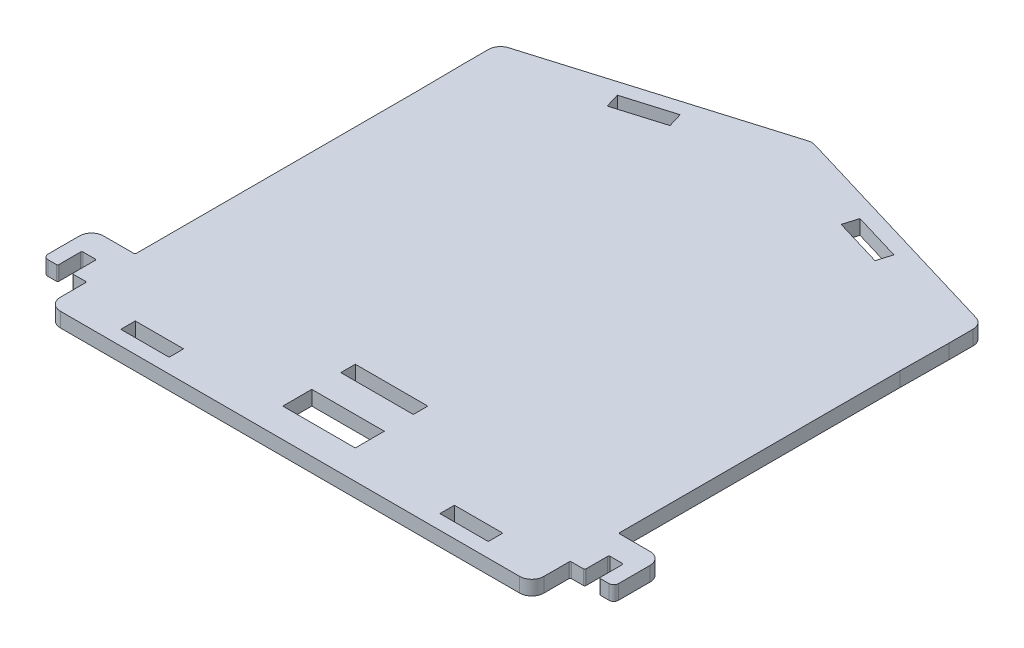
SolidWorks part; units mm, degrees
ref_plane "Alzado" through (0, 0, 0) normal (0, 0, 1) x (1, 0, 0)
ref_plane "Planta" through (0, 0, 0) normal (0, 1, 0) x (1, 0, 0)
ref_plane "Vista lateral" through (0, 0, 0) normal (1, 0, 0) x (0, 0, -1)
sketch "Croquis3" plane through (0, 0, 0) normal (0, 1, 0) x (1, 0, 0)
  line L3 (-50, -45) -> (50, -45)
  line L5 (-50, 45) -> (50, -45) construction
  line L6 (-50, -45) -> (50, 45) construction
  line L7 (-48.3179, 45.5346) -> (-0.6155, 59.8352)
  line L17 (0, 7.5742) -> (0, -7.5742) construction
  line L18 (-8.1342, 0) -> (8.1342, 0) construction
  line L19 (50, -30.05) -> (50, 28.1899)
  line L20 (56.5, -30.05) -> (50, -30.05)
  line L21 (59, -40.05) -> (59, -32.55)
  line L26 (56, -40.05) -> (59, -40.05)
  line L27 (56, -35.05) -> (56, -40.05)
  line L36 (-24.4667, 52.6849) -> (-23.5953, 49.7782) construction
  line L45 (50.1, 38.1899) -> (50, 28.1899)
  line L53 (-50.1, 43.1399) -> (-50.1, 38.1899)
  line L69 (-23.5953, 49.7782) -> (-18.5953, 51.2772)
  line L70 (-18.5953, 51.2772) -> (-17.696, 48.2772)
  line L71 (-23.5953, 49.7782) -> (-28.5953, 48.2793)
  line L72 (-28.5953, 48.2793) -> (-27.696, 45.2793)
  line L73 (-27.696, 45.2793) -> (-17.696, 48.2772)
  line L74 (28.5953, 48.2793) -> (27.696, 45.2793)
  line L75 (23.5953, 49.7782) -> (28.5953, 48.2793)
  line L76 (23.5953, 49.7782) -> (18.5953, 51.2772)
  line L77 (18.5953, 51.2772) -> (17.696, 48.2772)
  line L78 (27.696, 45.2793) -> (17.696, 48.2772)
  line L79 (48.3179, 45.5346) -> (0.6155, 59.8352)
  line L80 (50.1, 43.1399) -> (50.1, 38.1899)
  line L81 (-50.1, 38.1899) -> (-50, 28.1899)
  line L82 (53, -35.05) -> (56, -35.05)
  line L83 (53, -40.05) -> (53, -35.05)
  line L84 (-50, -45) -> (-50, -40.05)
  line L85 (-50, -40.05) -> (-53, -40.05)
  line L86 (-53, -40.05) -> (-53, -35.05)
  line L87 (-53, -35.05) -> (-56, -35.05)
  line L88 (-56, -35.05) -> (-56, -40.05)
  line L89 (-56, -40.05) -> (-59, -40.05)
  line L90 (-59, -40.05) -> (-59, -32.55)
  line L91 (-56.5, -30.05) -> (-50, -30.05)
  line L92 (-50, -30.05) -> (-50, 28.1899)
  line L93 (50, -40.05) -> (53, -40.05)
  line L94 (50, -45) -> (50, -40.05)
  arc A5 (-48.3179, 45.5346) -> (-50.1, 43.1399) centre (-47.6, 43.1399) ccw
  arc A9 (48.3179, 45.5346) -> (50.1, 43.1399) centre (47.6, 43.1399) cw
  arc A10 (-0.6155, 59.8352) -> (0.6155, 59.8352) centre (0, 57.2969) cw
  arc A11 (59, -32.55) -> (56.5, -30.05) centre (56.5, -32.55) ccw
  arc A12 (-59, -32.55) -> (-56.5, -30.05) centre (-56.5, -32.55) cw
  point P0 (0, 0)
  point P16 (0, 0)
  point P18 (0, 0)
  point P29 (0, 0)
  point P34 (-59, -30.05)
  point P53 (0, 60)
  point P59 (-23.5953, 49.7782)
  point P60 (-23.5953, 49.7782)
  point P66 (-50.1, 38.1899)
  point P94 (0, 45)
  dimension "D10" = 4.95
  dimension "D11" = 3
  dimension "D17" = 2.5
  dimension "D1" = 90
  dimension "D2" = 100
  dimension "D5" = 15
  dimension "D12" = 3
  dimension "D13" = 3
  dimension "D14" = 10
  dimension "D15" = 5
  dimension "D16" = 5
  dimension "D18" = 3
  dimension "D19" = 3
  dimension "D20" = 5
  dimension "D21" = 5
extrude "Saliente-Extruir1" add sketch "Croquis3" along normal blind 3
sketch "Croquis4" plane through (0, 3, 0) normal (0, 1, 0) x (1, 0, 0)
  line L5 (-28, -42) -> (28, -42) construction
  line L6 (-7.5, -42) -> (7.5, -42)
  line L7 (0, 9.5449) -> (0, -9.5449) construction
  line L12 (7.5, -42) -> (7.5, -36)
  line L14 (-8.1155, 0) -> (8.1155, 0) construction
  line L16 (-38, -45) -> (-28, -45)
  line L17 (-50, -45) -> (50, -45) construction
  line L18 (-38, -45) -> (-38, -42)
  line L19 (-38, -42) -> (-28, -42)
  line L20 (-28, -45) -> (-28, -42)
  line L24 (38, -42) -> (28, -42)
  line L25 (28, -45) -> (28, -42)
  line L26 (38, -45) -> (28, -45)
  line L27 (38, -45) -> (38, -42)
  line L28 (7.5, -36) -> (-7.5, -36)
  line L29 (-7.5, -36) -> (-7.5, -42)
  line L30 (0, -36) -> (0, -30) construction
  line L32 (-7.5, -30) -> (7.5, -30)
  line L36 (-32.75, -15.8561) -> (32.75, -15.8561) construction
  line L39 (7.5, -30) -> (7.5, -27)
  line L40 (7.5, -27) -> (-7.5, -27)
  line L41 (-7.5, -27) -> (-7.5, -30)
  point P3 (0, -42)
  point P11 (0, 0)
  point P16 (0, -30)
  point P23 (0, 0)
  point P29 (-38, -45)
  dimension "D4" = 3
  dimension "D6" = 3
  dimension "D1" = 6
  dimension "D2" = 15
  dimension "D3" = 6
  dimension "D7" = 10
extrude "Cortar-Extruir1" cut sketch "Croquis4" against normal mid plane 6
sketch "Croquis5" plane through (0, 0, 0) normal (0, 1, 0) x (1, 0, 0)
  line L0 (-50, -45) -> (50, -45)
  line L5 (50, -45) -> (50, -45.5)
  line L6 (47.5, -48) -> (-47.5, -48)
  line L7 (-50, -45.5) -> (-50, -45)
  arc A0 (50, -45.5) -> (47.5, -48) centre (47.5, -45.5) cw
  arc A1 (-47.5, -48) -> (-50, -45.5) centre (-47.5, -45.5) cw
  point P8 (-50, -48)
  dimension "D2" = 2.5
  dimension "D1" = 3
extrude "Saliente-Extruir2" add sketch "Croquis5" along normal blind 3
fillet "Redondeo1" radius 1 2 edges at (59, 1.5, 40.05) (-59, 1.5, 40.05)
fillet "Redondeo2" radius 0.25 12 edges at (-50, 1.5, 30.05) (50, 1.5, 30.05) (56, 1.5, 40.05) (56, 1.5, 35.05) (53, 1.5, 35.05) (53, 1.5, 40.05) (50, 1.5, 40.05) (-50, 1.5, 40.05) (-53, 1.5, 40.05) (-53, 1.5, 35.05) (-56, 1.5, 35.05) (-56, 1.5, 40.05)
